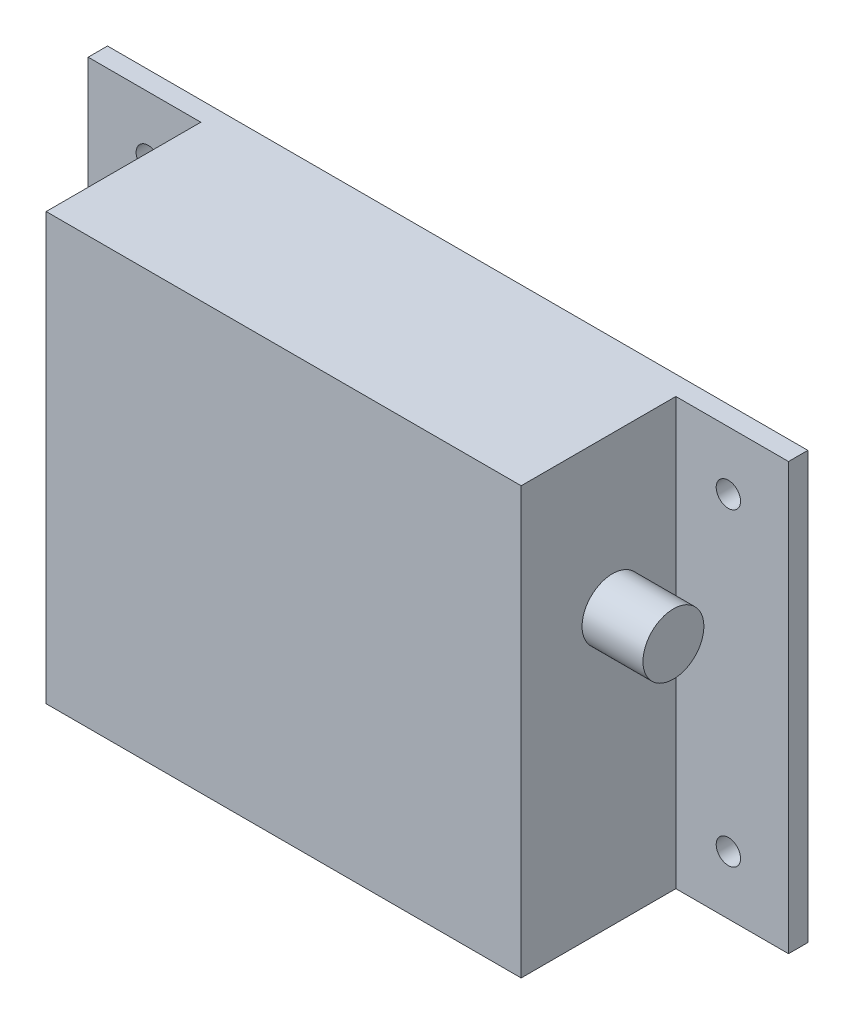
SolidWorks part; units mm, degrees
ref_plane "Front Plane" through (0, 0, 0) normal (0, 0, 1) x (1, 0, 0)
ref_plane "Top Plane" through (0, 0, 0) normal (0, 1, 0) x (1, 0, 0)
ref_plane "Right Plane" through (0, 0, 0) normal (1, 0, 0) x (0, 0, -1)
sketch "Sketch1" plane through (0, 0, 0) normal (0, 0, 1) x (1, 0, 0)
  line L1 (-39, 35) -> (39, 35)
  line L2 (-39, 35) -> (-39, -35)
  line L3 (-39, -35) -> (39, -35)
  line L4 (39, 35) -> (39, -35)
  line L5 (-39, 35) -> (39, -35) construction
  line L6 (-39, -35) -> (39, 35) construction
  point P0 (0, 0)
  dimension "D1" = 78
  dimension "D2" = 70
extrude "Boss-Extrude1" add sketch "Sketch1" along normal blind 28.575
sketch "Sketch2" plane through (0, 0, 0) normal (0, 0, -1) x (-1, 0, 0)
  line L0 (39, -35) -> (-39, -35) construction
  line L1 (-57.5, 35) -> (57.5, 35)
  line L2 (-57.5, 35) -> (-57.5, -35)
  line L3 (-57.5, -35) -> (57.5, -35)
  line L4 (57.5, 35) -> (57.5, -35)
  line L5 (-57.5, 35) -> (57.5, -35) construction
  line L6 (-57.5, -35) -> (57.5, 35) construction
  point P0 (0, 0)
  dimension "D1" = 115
extrude "Boss-Extrude2" add sketch "Sketch2" against normal blind 3.175
sketch "Sketch3" plane through (0, 0, 0) normal (0, 0, -1) x (-1, 0, 0)
  line L1 (47.625, -25.4) -> (-47.625, -25.4) construction
  line L2 (47.625, -25.4) -> (47.625, 25.4) construction
  line L3 (47.625, 25.4) -> (-47.625, 25.4) construction
  line L4 (-47.625, -25.4) -> (-47.625, 25.4) construction
  line L5 (47.625, -25.4) -> (-47.625, 25.4) construction
  line L6 (47.625, 25.4) -> (-47.625, -25.4) construction
  circle A0 centre (-47.625, 25.4) radius 2
  circle A1 centre (47.625, 25.4) radius 2
  circle A2 centre (47.625, -25.4) radius 2
  circle A3 centre (-47.625, -25.4) radius 2
  point P0 (0, 0)
  dimension "D1" = 4
  dimension "D2" = 95.25
  dimension "D3" = 50.8
extrude "Cut-Extrude1" cut sketch "Sketch3" against normal through all
sketch "Sketch4" plane through (39, 0, 0) normal (-1, 0, 0) x (0, 0, 1)
  line L1 (28.575, 35) -> (28.575, -35) construction
  line L2 (28.575, 35) -> (3.175, 35) construction
  circle A0 centre (13.575, 10) radius 5
  dimension "D1" = 25
  dimension "D2" = 15
  dimension "D3" = 10
extrude "Boss-Extrude3" add sketch "Sketch4" against normal blind 10
